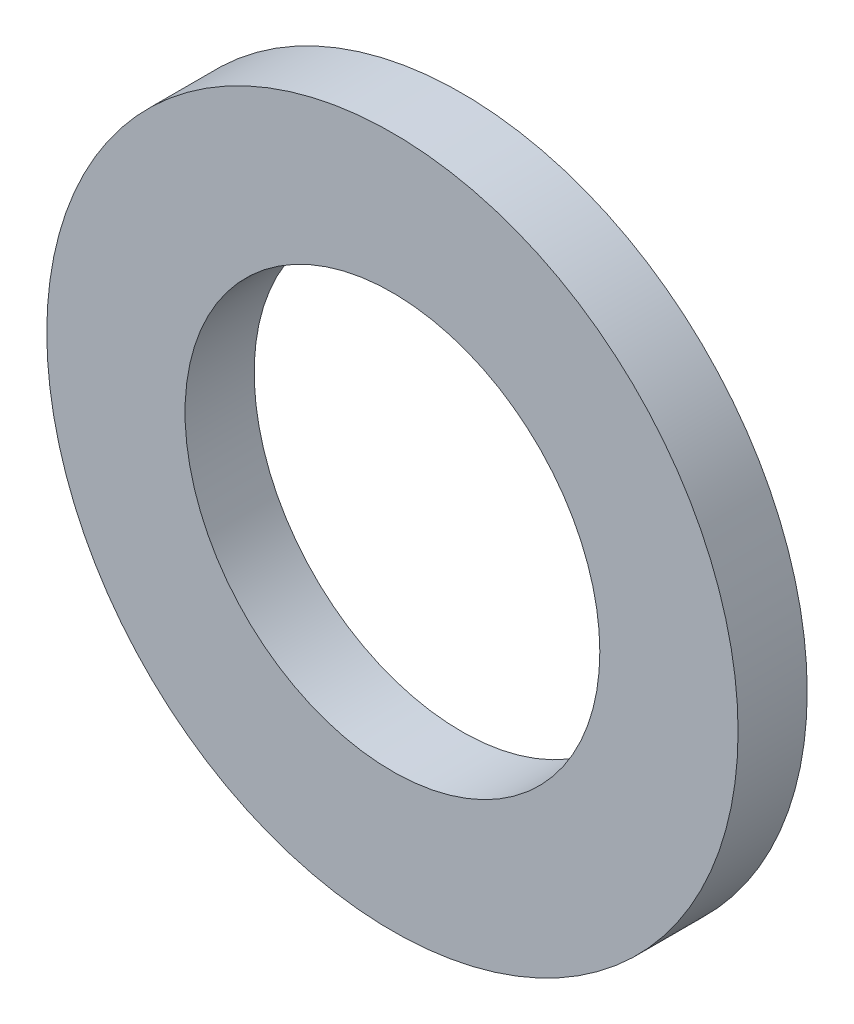
SolidWorks part; units mm, degrees
material "Beech"
ref_plane "Front Plane" through (0, 0, 0) normal (0, 0, 1) x (1, 0, 0)
ref_plane "Top Plane" through (0, 0, 0) normal (0, 1, 0) x (1, 0, 0)
ref_plane "Right Plane" through (0, 0, 0) normal (1, 0, 0) x (0, 0, -1)
sketch "Sketch1" plane through (0, 0, 0) normal (0, 0, 1) x (1, 0, 0)
  circle A0 centre (0, 0) radius 15.24
  circle A1 centre (0, 0) radius 25.4
  dimension "D1" = 30.48
  dimension "D2" = 50.8
extrude "Boss-Extrude1" add sketch "Sketch1" along normal blind 5.08
